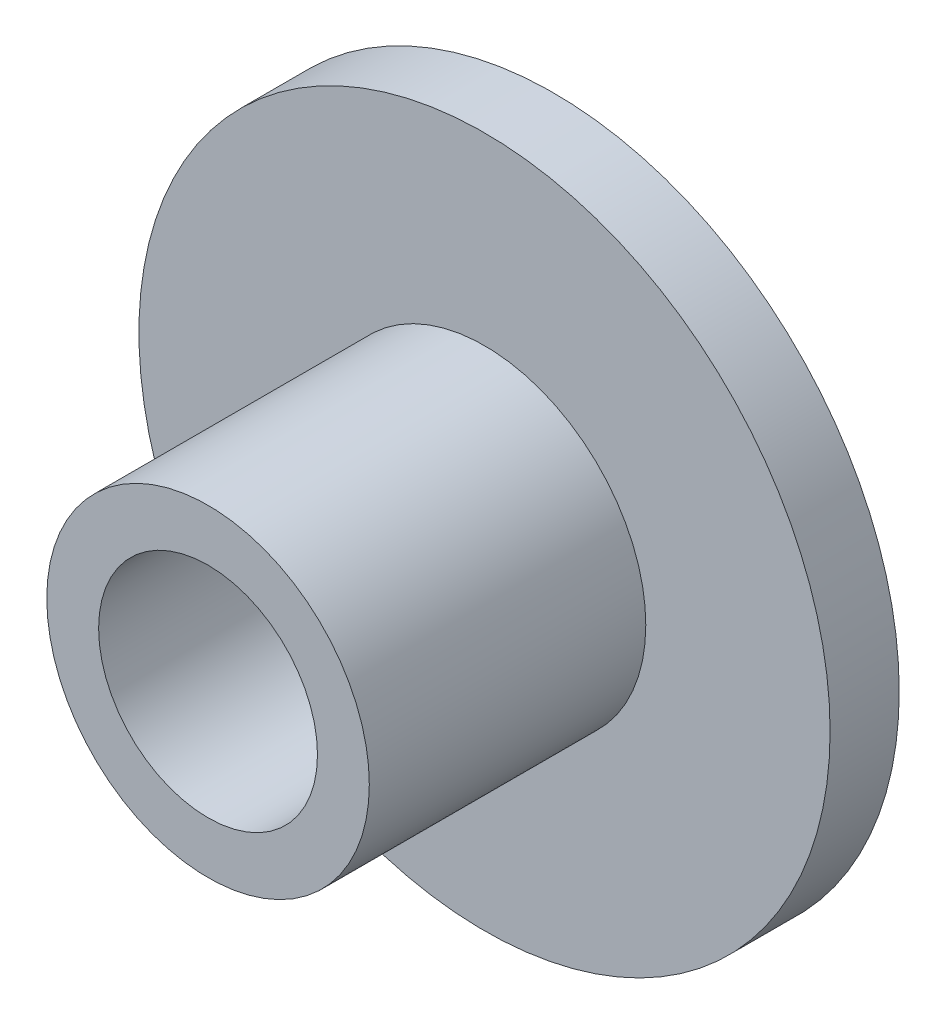
SolidWorks part; units mm, degrees
ref_plane "Front Plane" through (0, 0, 0) normal (0, 0, 1) x (1, 0, 0)
ref_plane "Top Plane" through (0, 0, 0) normal (0, 1, 0) x (1, 0, 0)
ref_plane "Right Plane" through (0, 0, 0) normal (1, 0, 0) x (0, 0, -1)
sketch "Sketch1" plane through (0, 0, 0) normal (0, 0, 1) x (1, 0, 0)
  circle A0 centre (0, 0) radius 15
  circle A1 centre (0, 0) radius 4.75
  dimension "D1" = 30
  dimension "D2" = 9.5
extrude "Boss-Extrude1" add sketch "Sketch1" along normal blind 15
sketch "Sketch2" plane through (0, 0, 15) normal (0, 0, 1) x (1, 0, 0)
  circle A0 centre (0, 0) radius 7
  circle A1 centre (0, 0) radius 15
  dimension "D1" = 14
extrude "Cut-Extrude1" cut sketch "Sketch2" against normal blind 12
